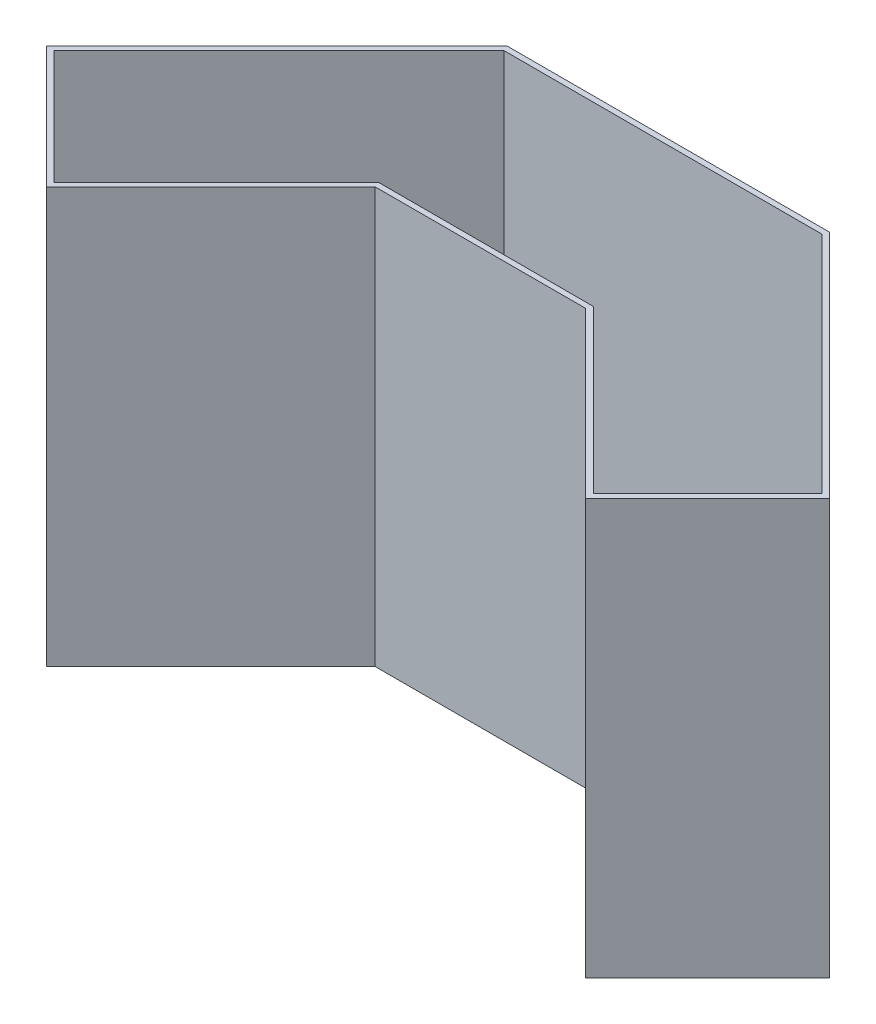
SolidWorks part; units mm, degrees
ref_plane "前视基准面" through (0, 0, 0) normal (0, 0, 1) x (1, 0, 0)
ref_plane "上视基准面" through (0, 0, 0) normal (0, 1, 0) x (1, 0, 0)
ref_plane "右视基准面" through (0, 0, 0) normal (1, 0, 0) x (0, 0, -1)
other "Configuration Table"
sketch "草图1" plane through (0, 0, 0) normal (0, 1, 0) x (1, 0, 0)
  line L0 (-57.4025, 0) -> (57.4025, 0)
  line L1 (57.4025, 0) -> (138.5819, -81.1794)
  line L2 (-38.8341, -63.8549) -> (38.8341, -63.8549)
  line L3 (38.8341, -63.8549) -> (97.3703, -122.3911)
  line L4 (138.5819, -81.1794) -> (97.3703, -122.3911)
  line L5 (0, 0) -> (0, -63.8549) construction
  line L6 (-138.5819, -81.1794) -> (-97.3703, -122.3911)
  line L7 (-57.4025, 0) -> (-138.5819, -81.1794)
  line L8 (-38.8341, -63.8549) -> (-97.3703, -122.3911)
  line L9 (-141.4104, -81.1794) -> (-97.3703, -125.2195)
  line L10 (-38.0056, -65.8549) -> (-97.3703, -125.2195)
  line L11 (-38.0056, -65.8549) -> (38.0056, -65.8549)
  line L12 (38.0056, -65.8549) -> (97.3703, -125.2195)
  line L13 (141.4104, -81.1794) -> (97.3703, -125.2195)
  line L14 (58.2309, 2) -> (141.4104, -81.1794)
  line L15 (-58.2309, 2) -> (58.2309, 2)
  line L16 (-58.2309, 2) -> (-141.4104, -81.1794)
  line L17 (-138.5819, -81.1794) -> (-138.5819, -195.9844) construction
  line L18 (-138.5819, -195.9844) -> (138.5819, -81.1794) construction
  point P2 (0, 0)
  dimension "D1" = 135
  dimension "D3" = 300
  dimension "D2" = 2
extrude "凸台-拉伸1" add sketch "草图1" along normal blind 150
